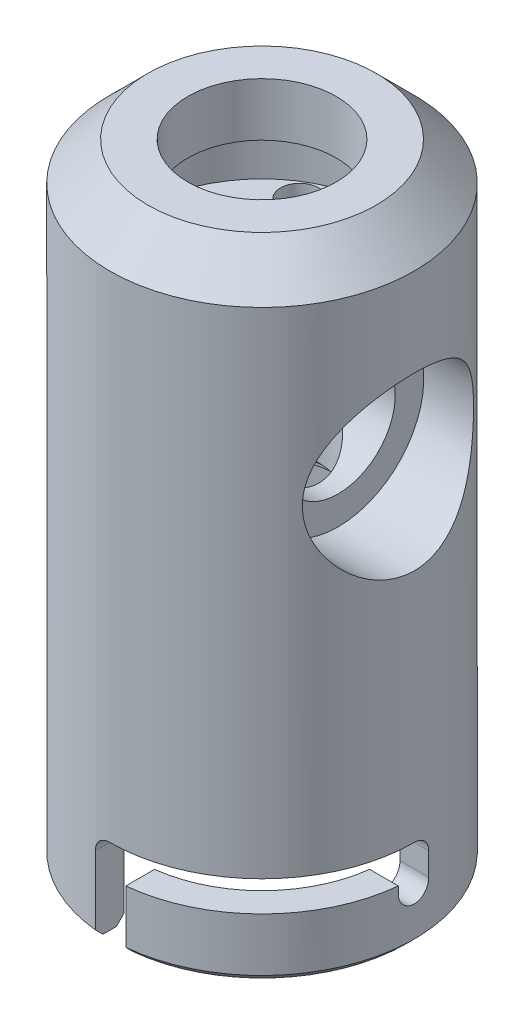
SolidWorks part; units mm, degrees
ref_plane "Front Plane" through (0, 0, 0) normal (0, 0, 1) x (1, 0, 0)
ref_plane "Top Plane" through (0, 0, 0) normal (0, 1, 0) x (1, 0, 0)
ref_plane "Right Plane" through (0, 0, 0) normal (1, 0, 0) x (0, 0, -1)
sketch "Sketch2" plane through (0, 0, 0) normal (0, 1, 0) x (1, 0, 0)
  circle A0 centre (0, 0) radius 20
  dimension "D1" = 40
extrude "Boss-Extrude1" add sketch "Sketch2" along normal blind 29 and the other way blind 53
chamfer "Chamfer1" distance 5 angle 45 1 edges at (0, 29, 20)
sketch "Sketch3" plane through (0, 0, 0) normal (0, 0, 1) x (1, 0, 0)
  line L0 (-20, 1.1469) -> (20, 1.1469) construction
  line L1 (20, -53) -> (20, 24) construction
  line L2 (20, 1.1469) -> (20, 12.3969)
  line L3 (20, 12.3969) -> (10, 12.3969)
  line L4 (10, 12.3969) -> (10, 8.6469)
  line L5 (10, 8.6469) -> (-11, 8.6469)
  line L6 (-11, 8.6469) -> (-15, 3.1469)
  line L7 (-15, 3.1469) -> (-19, 3.1469)
  line L8 (-19, 3.1469) -> (-19, 6.1469)
  line L9 (-19, 6.1469) -> (-20, 6.1469)
  line L10 (-20, 24) -> (-20, -53) construction
  line L11 (-20, 6.1469) -> (-20, 1.1469)
  line L12 (20, 1.1469) -> (-20, 1.1469)
  point P0 (20, 6.7719)
  dimension "D1" = 10
  dimension "D2" = 31
  dimension "D3" = 5
  dimension "D4" = 1
  dimension "D5" = 22.5
  dimension "D6" = 15
  dimension "D7" = 4
  dimension "D8" = 10
revolve "Cut-Revolve1" cut sketch "Sketch3" angle 360 about L0
sketch "Sketch4" plane through (0, 0, 0) normal (1, 0, 0) x (0, 0, -1)
  line L0 (0, 29) -> (0, -53) construction
  line L1 (15, 29) -> (-15, 29) construction
  line L2 (-20, -53) -> (20, -53) construction
  line L3 (0, -53) -> (-16.25, -53)
  line L4 (-16.25, -53) -> (-16.25, -14)
  line L5 (-16.25, -14) -> (-9.75, -14)
  line L6 (-9.75, -14) -> (-9.75, -12.6)
  line L7 (-9.75, -12.6) -> (-7.5, -12.6)
  line L8 (-7.5, -12.6) -> (-7.5, 1.1469)
  line L9 (-7.5, 1.1469) -> (0, 1.1469)
  line L10 (0, 29) -> (-9.75, 29)
  line L11 (-9.75, 29) -> (-9.75, 22)
  line L12 (-9.75, 22) -> (-16.25, 22)
  line L13 (-16.25, 22) -> (-16.25, 13)
  line L14 (-16.25, 13) -> (0, 13)
  circle A0 centre (0, 1.1469) radius 7.5 construction
  circle A1 centre (0, 1.1469) radius 7.5 construction
  dimension "D1" = 19.5
  dimension "D2" = 32.5
  dimension "D3" = 9
  dimension "D4" = 16
  dimension "D5" = 39
  dimension "D6" = 1.4
  dimension "D7" = 32.5
  dimension "D8" = 15
  dimension "D9" = 19.5
revolve "Cut-Revolve2" cut sketch "Sketch4" angle 360 about L0
sketch "Sketch5" plane through (0, 0, 0) normal (1, 0, 0) x (0, 0, -1)
  line L0 (0, -43) -> (0, -46) construction
  line L1 (2, -43) -> (2, -46)
  line L2 (-2, -43) -> (-2, -46)
  line L3 (-20, -53) -> (20, -53) construction
  line L5 (0, -41) -> (0, -53) construction
  arc A0 (2, -43) -> (-2, -43) centre (0, -43) ccw
  arc A1 (-2, -46) -> (2, -46) centre (0, -46) ccw
  point P3 (0, -44.5)
  dimension "D1" = 4
  dimension "D2" = 10
  dimension "D3" = 7
chamfer "Chamfer3" distance 1 angle 45 4 edges at (0, -12.6, 9.75) (0, -12.6, 7.5) (0, -53, 20) (0, -53, 16.25)
extrude "Cut-Extrude1" cut sketch "Sketch5" against normal through all both and the other way through all
sketch "Sketch6" plane through (0, 0, 0) normal (0, 0, 1) x (1, 0, 0)
  line L0 (0, -43) -> (0, -63) construction
  line L1 (2, -43) -> (2, -63)
  line L2 (-2, -43) -> (-2, -63)
  line L3 (-20, -53) -> (20, -53) construction
  arc A0 (2, -43) -> (-2, -43) centre (0, -43) ccw
  arc A1 (-2, -63) -> (2, -63) centre (0, -63) ccw
  point P3 (0, -53)
  point P10 (0, -53)
  dimension "D1" = 4
  dimension "D2" = 10
extrude "Cut-Extrude2" cut sketch "Sketch6" against normal through all both and the other way through all
sketch "Sketch9" plane through (0, 0, 0) normal (0, 0, 1) x (1, 0, 0)
  line L1 (0, -41) -> (39.404, -41)
  line L2 (0, -41) -> (0, -45)
  line L3 (0, -45) -> (39.404, -45)
  line L4 (39.404, -41) -> (39.404, -45)
  arc A0 (2, -43) -> (-2, -43) centre (0, -43) ccw construction
  dimension "D1" = 4
extrude "Cut-Extrude3" cut sketch "Sketch9" along normal through all
sketch "Sketch10" plane through (0, 0, 0) normal (0, 0, 1) x (1, 0, 0)
  line L1 (0, -41) -> (-32.4891, -41)
  line L2 (0, -41) -> (0, -45)
  line L3 (0, -45) -> (-32.4891, -45)
  line L4 (-32.4891, -41) -> (-32.4891, -45)
  dimension "D1" = 4
extrude "Cut-Extrude5" cut sketch "Sketch10" against normal through all
sketch "Sketch12" plane through (0, -14, 0) normal (0, -1, 0) x (1, 0, 0)
  line L0 (0, 7.5) -> (0, 0) construction
  line L1 (0, 0) -> (13.5, 0) construction
  line L2 (6.75, 11.6913) -> (0, 0) construction
  line L3 (0, 0) -> (0, 13.5) construction
  line L4 (-6.75, 11.6913) -> (0, 0) construction
  line L5 (-6.75, -11.6913) -> (0, 0) construction
  line L6 (6.75, -11.6913) -> (0, 0) construction
  arc A0 (0, 7.5) -> (0, -7.5) centre (0, 0) ccw construction
  circle A1 centre (0, 0) radius 13.5 construction
  circle A2 centre (6.75, 11.6913) radius 2.5
  circle A3 centre (-6.75, 11.6913) radius 2.5
  circle A4 centre (6.75, -11.6913) radius 2.5
  circle A5 centre (-6.75, -11.6913) radius 2.5
  dimension "D1" = 27
  dimension "D3" = 5
  dimension "D2" = 30
extrude "Cut-Extrude6" cut sketch "Sketch12" against normal up to surface (27 mm away) up to face at (0, 13, 16.25)
